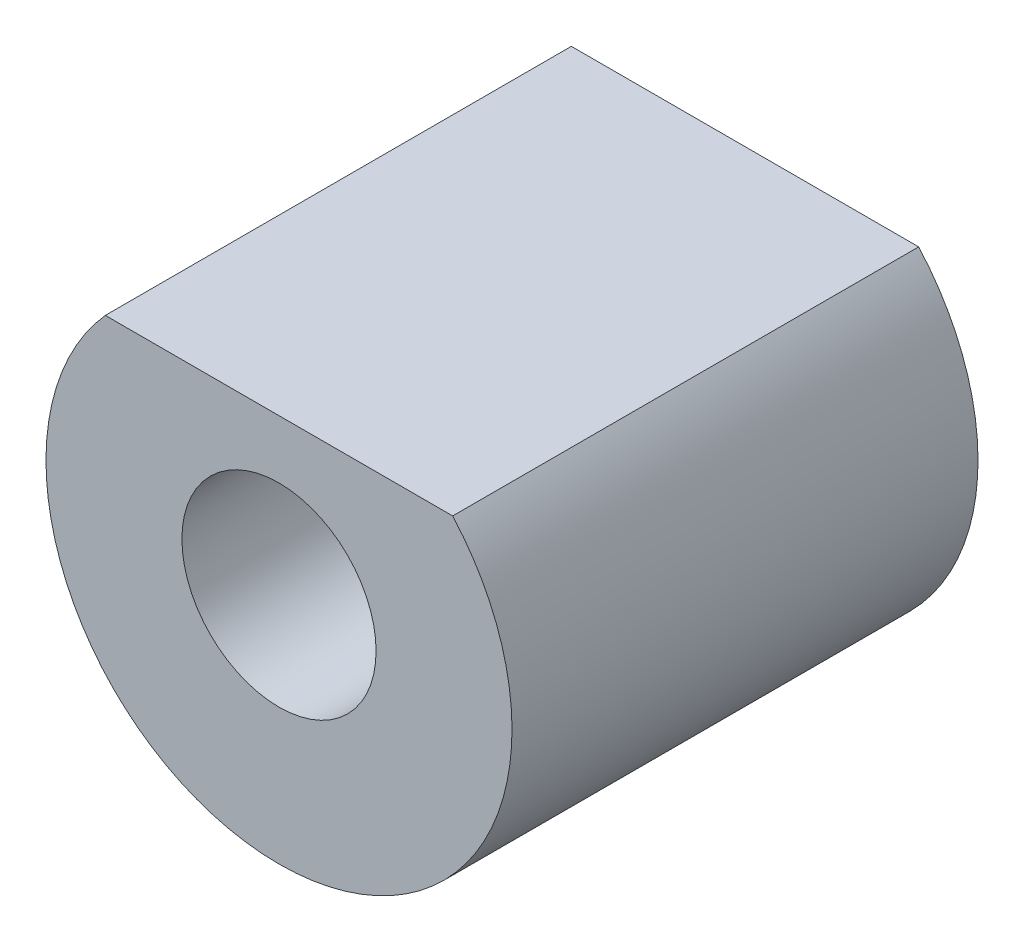
SolidWorks part; units mm, degrees
ref_plane "Front Plane" through (0, 0, 0) normal (0, 0, 1) x (1, 0, 0)
ref_plane "Top Plane" through (0, 0, 0) normal (0, 1, 0) x (1, 0, 0)
ref_plane "Right Plane" through (0, 0, 0) normal (1, 0, 0) x (0, 0, -1)
sketch "Sketch1" plane through (0, 0, 0) normal (0, 0, 1) x (1, 0, 0)
  line L0 (-2.2361, 2) -> (2.2361, 2)
  circle A0 centre (0, 0) radius 1.25
  arc A1 (-2.2361, 2) -> (2.2361, 2) centre (0, 0) ccw
  dimension "D1" = 2.5
  dimension "D2" = 3
  dimension "D3" = 2
extrude "Boss-Extrude1" add sketch "Sketch1" along normal blind 6
